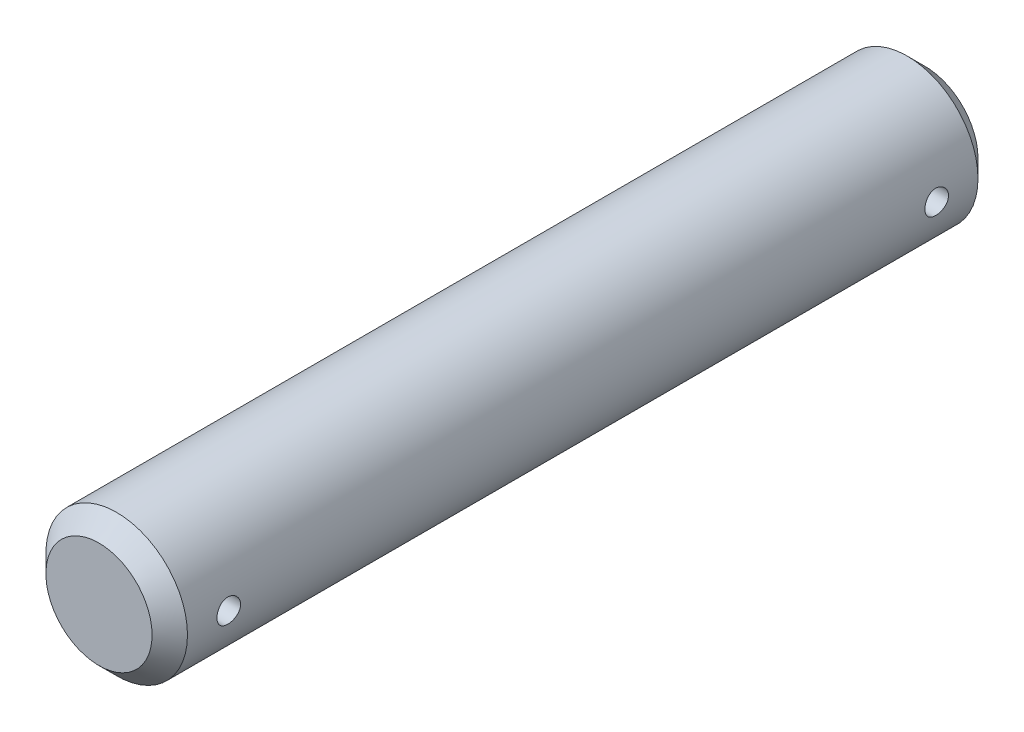
SolidWorks part; units mm, degrees
material "Stainless Steel (ferritic)"
ref_plane "Front Plane" through (0, 0, 0) normal (0, 0, 1) x (1, 0, 0)
ref_plane "Top Plane" through (0, 0, 0) normal (0, 1, 0) x (1, 0, 0)
ref_plane "Right Plane" through (0, 0, 0) normal (1, 0, 0) x (0, 0, -1)
sketch "Sketch1" plane through (0, 0, 0) normal (1, 0, 0) x (0, 0, -1)
  line L0 (-35, 0) -> (35, 0) construction
  line L1 (35, 0) -> (35, 4.5)
  line L2 (35, 4.5) -> (33.5, 6)
  line L3 (33.5, 6) -> (-33.5, 6)
  line L4 (-33.5, 6) -> (-35, 4.5)
  line L5 (-35, 4.5) -> (-35, 0)
  line L6 (35, 0) -> (-35, 0)
  point P4 (0, 0)
  point P11 (0, 6)
  dimension "D1" = 70
  dimension "D2" = 12
  dimension "D3" = 1.5
revolve "Revolve1" add sketch "Sketch1" angle 360 about L0
sketch "Sketch2" plane through (0, 0, 0) normal (1, 0, 0) x (0, 0, -1)
  line L0 (0, 6) -> (0, -6) construction
  line L1 (33.5, 6) -> (-33.5, 6) construction
  line L2 (-33.5, -6) -> (33.5, -6) construction
  line L3 (33.5, 6) -> (33.5, -6) construction
  circle A0 centre (30, 0) radius 1
  circle A1 centre (-30, 0) radius 1
  dimension "D1" = 2
  dimension "D2" = 3.5
extrude "Cut-Extrude1" cut sketch "Sketch2" against normal through all both and the other way through all
